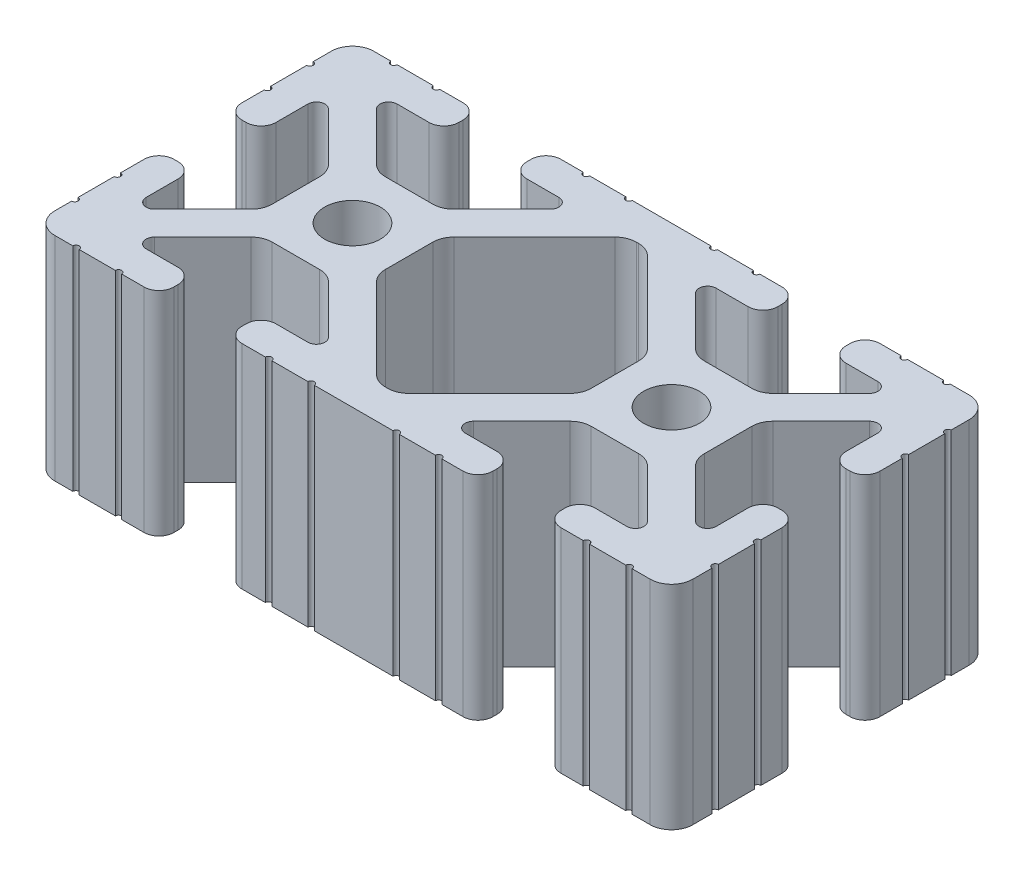
SolidWorks part; units mm, degrees
ref_plane "Front" through (0, 0, 0) normal (0, 0, 1) x (1, 0, 0)
ref_plane "Top" through (0, 0, 0) normal (0, 1, 0) x (1, 0, 0)
ref_plane "Right" through (0, 0, 0) normal (1, 0, 0) x (0, 0, -1)
sketch "Sketch1" plane through (0, 0, 0) normal (0, 1, 0) x (1, 0, 0)
  line L0 (-12.2936, -2.8306) -> (-12.2936, 2.8306)
  line L1 (-1.9343, -14.2421) -> (-11.5497, -4.6267)
  line L2 (-0.1382, -14.986) -> (0.1382, -14.986)
  line L3 (11.5497, -4.6267) -> (1.9343, -14.2421)
  line L4 (12.2936, 2.8306) -> (12.2936, -2.8306)
  line L5 (1.9343, 14.2421) -> (11.5497, 4.6267)
  line L6 (0.1382, 14.986) -> (-0.1382, 14.986)
  line L7 (-11.5497, 4.6267) -> (-1.9343, 14.2421)
  line L8 (27.4208, 19.05) -> (24.892, 19.05)
  line L9 (23.114, 17.272) -> (23.114, 16.764)
  line L10 (24.892, 14.986) -> (28.7095, 14.986)
  line L11 (29.4279, 13.2516) -> (23.6767, 7.5003)
  line L12 (21.8806, 6.7564) -> (16.2194, 6.7564)
  line L13 (14.4233, 7.5003) -> (8.6721, 13.2516)
  line L14 (9.3905, 14.986) -> (13.208, 14.986)
  line L15 (14.986, 16.764) -> (14.986, 17.272)
  line L16 (13.208, 19.05) -> (10.541, 19.05)
  line L17 (9.779, 19.05) -> (5.461, 19.05)
  line L18 (4.699, 19.05) -> (-4.699, 19.05)
  line L19 (-5.461, 19.05) -> (-9.779, 19.05)
  line L20 (-10.541, 19.05) -> (-13.208, 19.05)
  line L21 (-14.986, 17.272) -> (-14.986, 16.764)
  line L22 (-13.208, 14.986) -> (-9.3905, 14.986)
  line L23 (-8.6721, 13.2516) -> (-14.4233, 7.5003)
  line L24 (-16.2194, 6.7564) -> (-21.8806, 6.7564)
  line L25 (-23.6767, 7.5003) -> (-29.4279, 13.2516)
  line L26 (-28.7095, 14.986) -> (-24.892, 14.986)
  line L27 (-23.114, 16.764) -> (-23.114, 17.272)
  line L28 (-24.892, 19.05) -> (-27.6972, 19.05)
  line L29 (-28.4592, 19.05) -> (-32.7772, 19.05)
  line L30 (-33.5392, 19.05) -> (-35.56, 19.05)
  line L31 (-38.1, 16.51) -> (-38.1, 14.351)
  line L32 (-38.1, 13.589) -> (-38.1, 9.271)
  line L33 (-38.1, 8.509) -> (-38.1, 5.842)
  line L34 (-36.322, 4.064) -> (-35.814, 4.064)
  line L35 (-34.036, 5.842) -> (-34.036, 9.6595)
  line L36 (-32.3016, 10.3779) -> (-26.5503, 4.6267)
  line L37 (-25.8064, 2.8306) -> (-25.8064, -2.8306)
  line L38 (-26.5503, -4.6267) -> (-32.3016, -10.3779)
  line L39 (-34.036, -9.6595) -> (-34.036, -5.842)
  line L40 (-35.814, -4.064) -> (-36.322, -4.064)
  line L41 (-38.1, -5.842) -> (-38.1, -8.6472)
  line L42 (-38.1, -9.4092) -> (-38.1, -13.7272)
  line L43 (-38.1, -14.4892) -> (-38.1, -16.51)
  line L44 (-35.56, -19.05) -> (-33.401, -19.05)
  line L45 (-32.639, -19.05) -> (-28.321, -19.05)
  line L46 (-27.559, -19.05) -> (-24.892, -19.05)
  line L47 (-23.114, -17.272) -> (-23.114, -16.764)
  line L48 (-24.892, -14.986) -> (-28.7095, -14.986)
  line L49 (-29.4279, -13.2516) -> (-23.6767, -7.5003)
  line L50 (-21.8806, -6.7564) -> (-16.2194, -6.7564)
  line L51 (-14.4233, -7.5003) -> (-8.6721, -13.2516)
  line L52 (-9.3905, -14.986) -> (-13.208, -14.986)
  line L53 (-14.986, -16.764) -> (-14.986, -17.272)
  line L54 (-13.208, -19.05) -> (-10.4028, -19.05)
  line L55 (-9.6408, -19.05) -> (-5.3228, -19.05)
  line L56 (-4.5608, -19.05) -> (4.8372, -19.05)
  line L57 (5.5992, -19.05) -> (9.9172, -19.05)
  line L58 (10.6792, -19.05) -> (13.208, -19.05)
  line L59 (14.986, -17.272) -> (14.986, -16.764)
  line L60 (13.208, -14.986) -> (9.3905, -14.986)
  line L61 (8.6721, -13.2516) -> (14.4233, -7.5003)
  line L62 (16.2194, -6.7564) -> (21.8806, -6.7564)
  line L63 (23.6767, -7.5003) -> (29.4279, -13.2516)
  line L64 (28.7095, -14.986) -> (24.892, -14.986)
  line L65 (23.114, -16.764) -> (23.114, -17.272)
  line L66 (24.892, -19.05) -> (27.559, -19.05)
  line L67 (28.321, -19.05) -> (32.639, -19.05)
  line L68 (33.401, -19.05) -> (35.56, -19.05)
  line L69 (38.1, -16.51) -> (38.1, -14.2128)
  line L70 (38.1, -13.4508) -> (38.1, -9.1328)
  line L71 (38.1, -8.3708) -> (38.1, -5.842)
  line L72 (36.322, -4.064) -> (35.814, -4.064)
  line L73 (34.036, -5.842) -> (34.036, -9.6595)
  line L74 (32.3016, -10.3779) -> (26.5503, -4.6267)
  line L75 (25.8064, -2.8306) -> (25.8064, 2.8306)
  line L76 (26.5503, 4.6267) -> (32.3016, 10.3779)
  line L77 (34.036, 9.6595) -> (34.036, 5.842)
  line L78 (35.814, 4.064) -> (36.322, 4.064)
  line L79 (38.1, 5.842) -> (38.1, 8.509)
  line L80 (38.1, 9.271) -> (38.1, 13.589)
  line L81 (38.1, 14.351) -> (38.1, 16.51)
  line L82 (35.56, 19.05) -> (33.2628, 19.05)
  line L83 (32.5008, 19.05) -> (28.1828, 19.05)
  circle A0 centre (19.05, 0) radius 3.3274
  circle A1 centre (-19.05, 0) radius 3.3274
  arc A2 (-11.5497, 4.6267) -> (-12.2936, 2.8306) centre (-9.7536, 2.8306) ccw
  arc A3 (-12.2936, -2.8306) -> (-11.5497, -4.6267) centre (-9.7536, -2.8306) ccw
  arc A4 (-1.9343, -14.2421) -> (-0.1382, -14.986) centre (-0.1382, -12.446) ccw
  arc A5 (0.1382, -14.986) -> (1.9343, -14.2421) centre (0.1382, -12.446) ccw
  arc A6 (11.5497, -4.6267) -> (12.2936, -2.8306) centre (9.7536, -2.8306) ccw
  arc A7 (12.2936, 2.8306) -> (11.5497, 4.6267) centre (9.7536, 2.8306) ccw
  arc A8 (1.9343, 14.2421) -> (0.1382, 14.986) centre (0.1382, 12.446) ccw
  arc A9 (-0.1382, 14.986) -> (-1.9343, 14.2421) centre (-0.1382, 12.446) ccw
  arc A10 (27.4208, 19.05) -> (28.1828, 19.05) centre (27.8018, 19.05) ccw
  arc A11 (24.892, 19.05) -> (23.114, 17.272) centre (24.892, 17.272) ccw
  arc A12 (23.114, 16.764) -> (24.892, 14.986) centre (24.892, 16.764) ccw
  arc A13 (29.4279, 13.2516) -> (28.7095, 14.986) centre (28.7095, 13.97) ccw
  arc A14 (21.8806, 6.7564) -> (23.6767, 7.5003) centre (21.8806, 9.2964) ccw
  arc A15 (14.4233, 7.5003) -> (16.2194, 6.7564) centre (16.2194, 9.2964) ccw
  arc A16 (9.3905, 14.986) -> (8.6721, 13.2516) centre (9.3905, 13.97) ccw
  arc A17 (13.208, 14.986) -> (14.986, 16.764) centre (13.208, 16.764) ccw
  arc A18 (14.986, 17.272) -> (13.208, 19.05) centre (13.208, 17.272) ccw
  arc A19 (9.779, 19.05) -> (10.541, 19.05) centre (10.16, 19.05) ccw
  arc A20 (4.699, 19.05) -> (5.461, 19.05) centre (5.08, 19.05) ccw
  arc A21 (-5.461, 19.05) -> (-4.699, 19.05) centre (-5.08, 19.05) ccw
  arc A22 (-10.541, 19.05) -> (-9.779, 19.05) centre (-10.16, 19.05) ccw
  arc A23 (-13.208, 19.05) -> (-14.986, 17.272) centre (-13.208, 17.272) ccw
  arc A24 (-14.986, 16.764) -> (-13.208, 14.986) centre (-13.208, 16.764) ccw
  arc A25 (-8.6721, 13.2516) -> (-9.3905, 14.986) centre (-9.3905, 13.97) ccw
  arc A26 (-16.2194, 6.7564) -> (-14.4233, 7.5003) centre (-16.2194, 9.2964) ccw
  arc A27 (-23.6767, 7.5003) -> (-21.8806, 6.7564) centre (-21.8806, 9.2964) ccw
  arc A28 (-28.7095, 14.986) -> (-29.4279, 13.2516) centre (-28.7095, 13.97) ccw
  arc A29 (-24.892, 14.986) -> (-23.114, 16.764) centre (-24.892, 16.764) ccw
  arc A30 (-23.114, 17.272) -> (-24.892, 19.05) centre (-24.892, 17.272) ccw
  arc A31 (-28.4592, 19.05) -> (-27.6972, 19.05) centre (-28.0782, 19.05) ccw
  arc A32 (-33.5392, 19.05) -> (-32.7772, 19.05) centre (-33.1582, 19.05) ccw
  arc A33 (-35.56, 19.05) -> (-38.1, 16.51) centre (-35.56, 16.51) ccw
  arc A34 (-38.1, 13.589) -> (-38.1, 14.351) centre (-38.1, 13.97) ccw
  arc A35 (-38.1, 8.509) -> (-38.1, 9.271) centre (-38.1, 8.89) ccw
  arc A36 (-38.1, 5.842) -> (-36.322, 4.064) centre (-36.322, 5.842) ccw
  arc A37 (-35.814, 4.064) -> (-34.036, 5.842) centre (-35.814, 5.842) ccw
  arc A38 (-32.3016, 10.3779) -> (-34.036, 9.6595) centre (-33.02, 9.6595) ccw
  arc A39 (-25.8064, 2.8306) -> (-26.5503, 4.6267) centre (-28.3464, 2.8306) ccw
  arc A40 (-26.5503, -4.6267) -> (-25.8064, -2.8306) centre (-28.3464, -2.8306) ccw
  arc A41 (-34.036, -9.6595) -> (-32.3016, -10.3779) centre (-33.02, -9.6595) ccw
  arc A42 (-34.036, -5.842) -> (-35.814, -4.064) centre (-35.814, -5.842) ccw
  arc A43 (-36.322, -4.064) -> (-38.1, -5.842) centre (-36.322, -5.842) ccw
  arc A44 (-38.1, -9.4092) -> (-38.1, -8.6472) centre (-38.1, -9.0282) ccw
  arc A45 (-38.1, -14.4892) -> (-38.1, -13.7272) centre (-38.1, -14.1082) ccw
  arc A46 (-38.1, -16.51) -> (-35.56, -19.05) centre (-35.56, -16.51) ccw
  arc A47 (-32.639, -19.05) -> (-33.401, -19.05) centre (-33.02, -19.05) ccw
  arc A48 (-27.559, -19.05) -> (-28.321, -19.05) centre (-27.94, -19.05) ccw
  arc A49 (-24.892, -19.05) -> (-23.114, -17.272) centre (-24.892, -17.272) ccw
  arc A50 (-23.114, -16.764) -> (-24.892, -14.986) centre (-24.892, -16.764) ccw
  arc A51 (-29.4279, -13.2516) -> (-28.7095, -14.986) centre (-28.7095, -13.97) ccw
  arc A52 (-21.8806, -6.7564) -> (-23.6767, -7.5003) centre (-21.8806, -9.2964) ccw
  arc A53 (-14.4233, -7.5003) -> (-16.2194, -6.7564) centre (-16.2194, -9.2964) ccw
  arc A54 (-9.3905, -14.986) -> (-8.6721, -13.2516) centre (-9.3905, -13.97) ccw
  arc A55 (-13.208, -14.986) -> (-14.986, -16.764) centre (-13.208, -16.764) ccw
  arc A56 (-14.986, -17.272) -> (-13.208, -19.05) centre (-13.208, -17.272) ccw
  arc A57 (-9.6408, -19.05) -> (-10.4028, -19.05) centre (-10.0218, -19.05) ccw
  arc A58 (-4.5608, -19.05) -> (-5.3228, -19.05) centre (-4.9418, -19.05) ccw
  arc A59 (5.5992, -19.05) -> (4.8372, -19.05) centre (5.2182, -19.05) ccw
  arc A60 (10.6792, -19.05) -> (9.9172, -19.05) centre (10.2982, -19.05) ccw
  arc A61 (13.208, -19.05) -> (14.986, -17.272) centre (13.208, -17.272) ccw
  arc A62 (14.986, -16.764) -> (13.208, -14.986) centre (13.208, -16.764) ccw
  arc A63 (8.6721, -13.2516) -> (9.3905, -14.986) centre (9.3905, -13.97) ccw
  arc A64 (16.2194, -6.7564) -> (14.4233, -7.5003) centre (16.2194, -9.2964) ccw
  arc A65 (23.6767, -7.5003) -> (21.8806, -6.7564) centre (21.8806, -9.2964) ccw
  arc A66 (28.7095, -14.986) -> (29.4279, -13.2516) centre (28.7095, -13.97) ccw
  arc A67 (24.892, -14.986) -> (23.114, -16.764) centre (24.892, -16.764) ccw
  arc A68 (23.114, -17.272) -> (24.892, -19.05) centre (24.892, -17.272) ccw
  arc A69 (28.321, -19.05) -> (27.559, -19.05) centre (27.94, -19.05) ccw
  arc A70 (33.401, -19.05) -> (32.639, -19.05) centre (33.02, -19.05) ccw
  arc A71 (35.56, -19.05) -> (38.1, -16.51) centre (35.56, -16.51) ccw
  arc A72 (38.1, -13.4508) -> (38.1, -14.2128) centre (38.1, -13.8318) ccw
  arc A73 (38.1, -8.3708) -> (38.1, -9.1328) centre (38.1, -8.7518) ccw
  arc A74 (38.1, -5.842) -> (36.322, -4.064) centre (36.322, -5.842) ccw
  arc A75 (35.814, -4.064) -> (34.036, -5.842) centre (35.814, -5.842) ccw
  arc A76 (32.3016, -10.3779) -> (34.036, -9.6595) centre (33.02, -9.6595) ccw
  arc A77 (25.8064, -2.8306) -> (26.5503, -4.6267) centre (28.3464, -2.8306) ccw
  arc A78 (26.5503, 4.6267) -> (25.8064, 2.8306) centre (28.3464, 2.8306) ccw
  arc A79 (34.036, 9.6595) -> (32.3016, 10.3779) centre (33.02, 9.6595) ccw
  arc A80 (34.036, 5.842) -> (35.814, 4.064) centre (35.814, 5.842) ccw
  arc A81 (36.322, 4.064) -> (38.1, 5.842) centre (36.322, 5.842) ccw
  arc A82 (38.1, 9.271) -> (38.1, 8.509) centre (38.1, 8.89) ccw
  arc A83 (38.1, 14.351) -> (38.1, 13.589) centre (38.1, 13.97) ccw
  arc A84 (38.1, 16.51) -> (35.56, 19.05) centre (35.56, 16.51) ccw
  arc A85 (32.5008, 19.05) -> (33.2628, 19.05) centre (32.8818, 19.05) ccw
extrude "Boss-Extrude1" add sketch "Sketch1" along normal blind 25.4
